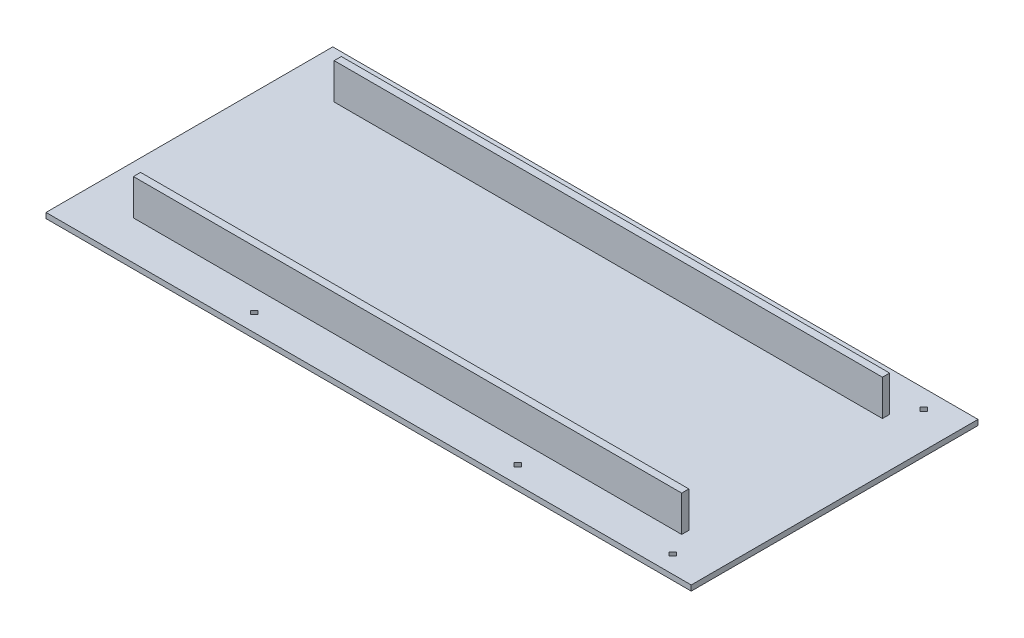
SolidWorks part; units mm, degrees
ref_plane "前视基准面" through (0, 0, 0) normal (0, 0, 1) x (1, 0, 0)
ref_plane "上视基准面" through (0, 0, 0) normal (0, 1, 0) x (1, 0, 0)
ref_plane "右视基准面" through (0, 0, 0) normal (1, 0, 0) x (0, 0, -1)
other "Configuration Table"
sketch "草图1" plane through (0, 0, 0) normal (0, 1, 0) x (1, 0, 0)
  line L0 (-62.069, 0) -> (62.4738, 0) construction
  line L1 (0, 36.904) -> (0, -36.6342) construction
  line L2 (37.76, 35) -> (36.76, 34)
  line L3 (-90, 40.1349) -> (90, 40.1349)
  line L4 (-90, 40.1349) -> (-90, -39.8651)
  line L5 (-90, -39.8651) -> (90, -39.8651)
  line L6 (90, 40.1349) -> (90, -39.8651)
  line L7 (-90, 40.1349) -> (90, -39.8651) construction
  line L8 (-90, -39.8651) -> (90, 40.1349) construction
  line L9 (-36.76, 34) -> (-35.76, 35)
  line L10 (-35.76, 35) -> (-36.76, 36)
  line L11 (-36.76, 36) -> (-37.76, 35)
  line L12 (-37.76, 35) -> (-36.76, 34)
  line L13 (36.76, 36) -> (37.76, 35)
  line L14 (35.76, 35) -> (36.76, 36)
  line L15 (36.76, 34) -> (35.76, 35)
  line L16 (36.76, -36) -> (37.76, -35)
  line L17 (35.76, -35) -> (36.76, -36)
  line L18 (36.76, -34) -> (35.76, -35)
  line L19 (37.76, -35) -> (36.76, -34)
  line L20 (-37.76, -35) -> (-36.76, -34)
  line L21 (-36.76, -36) -> (-37.76, -35)
  line L22 (-35.76, -35) -> (-36.76, -36)
  line L23 (-36.76, -34) -> (-35.76, -35)
  line L24 (81, -35) -> (80, -36)
  line L25 (80, 36) -> (79, 35)
  line L26 (79, 35) -> (80, 34)
  line L27 (80, 34) -> (81, 35)
  line L28 (81, 35) -> (80, 36)
  line L29 (80, -34) -> (81, -35)
  line L30 (79, -35) -> (80, -34)
  line L31 (80, -36) -> (79, -35)
  circle A0 centre (-36.76, 35) radius 0.7071 construction
  circle A1 centre (80, 35) radius 0.7071 construction
  point P5 (0, 0.1349)
  dimension "D1" = 180
  dimension "D2" = 80
  dimension "D3" = 36.76
  dimension "35" = 35
  dimension "D4" = 2
  dimension "D5" = 35
  dimension "D6" = 2
  dimension "D7" = 80
extrude "凸台-拉伸1" add sketch "草图1" along normal blind 1.5
sketch "草图2" plane through (0, 1.5, 0) normal (0, 1, 0) x (1, 0, 0)
  line L0 (-95.5708, 0) -> (106.7077, 0) construction
  line L1 (-76.4768, 27) -> (76.4768, 27)
  line L2 (-76.4768, 27) -> (-76.4768, 29)
  line L3 (-76.4768, 29) -> (76.4768, 29)
  line L4 (76.4768, 27) -> (76.4768, 29)
  line L5 (-76.4768, 27) -> (76.4768, 29) construction
  line L6 (-76.4768, 29) -> (76.4768, 27) construction
  line L7 (-76.4768, -29) -> (76.4768, -29)
  line L8 (76.4768, -27) -> (76.4768, -29)
  line L9 (-76.4768, -27) -> (76.4768, -27)
  line L10 (-76.4768, -27) -> (-76.4768, -29)
  point P0 (0, 28)
  dimension "D1" = 2
  dimension "D2" = 28
extrude "凸台-拉伸2" add sketch "草图2" along normal blind 10
